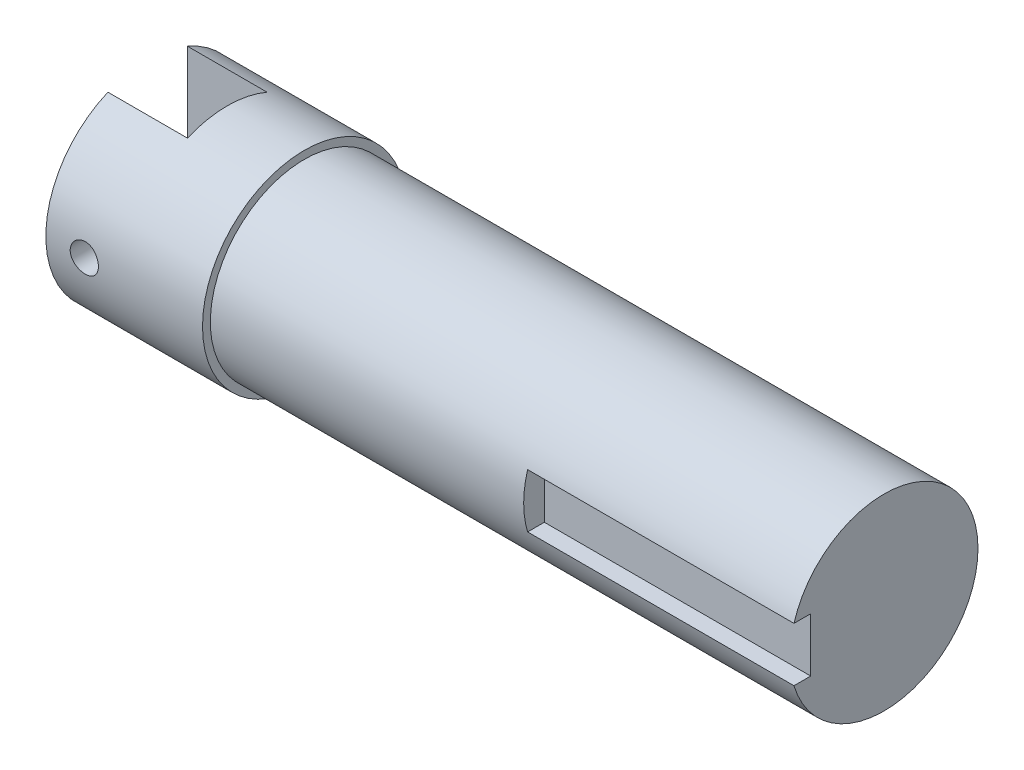
SolidWorks part; units mm, degrees
ref_plane "Front Plane" through (0, 0, 0) normal (1, 0, 0) x (0, 1, 0)
ref_plane "Top Plane" through (0, 0, 0) normal (0, 0, 1) x (0, 1, 0)
ref_plane "Right Plane" through (0, 0, 0) normal (0, 1, 0) x (-1, 0, 0)
sketch "Sketch1" plane through (0, 0, 0) normal (1, 0, 0) x (0, 1, 0)
  circle A0 centre (0, 0) radius 30
  dimension "D1" = 60
extrude "Boss-Extrude1" add sketch "Sketch1" along normal blind 185
sketch "Sketch2" plane through (0, 0, 0) normal (-1, 0, 0) x (0, 0, 1)
  circle A0 centre (0, 0) radius 32.5
  dimension "D1" = 65
extrude "Boss-Extrude2" add sketch "Sketch2" along normal blind 50
sketch "Sketch3" plane through (185, 0, 0) normal (1, 0, 0) x (0, 1, 0)
  line L0 (0, 30) -> (0, 23.4) construction
  line L1 (-8.6135, 34.4) -> (8.6135, 34.4)
  line L2 (-8.6135, 34.4) -> (-8.6135, 23.4)
  line L3 (-8.6135, 23.4) -> (8.6135, 23.4)
  line L4 (8.6135, 34.4) -> (8.6135, 23.4)
  circle A4 centre (0, 0) radius 30 construction
  circle A5 centre (0, 0) radius 30 construction
  point P4 (0, 23.4)
  dimension "D1" = 17.227
  dimension "D3" = 6.6
  dimension "D2" = 11
extrude "Cut-Extrude1" cut sketch "Sketch3" against normal blind 85
sketch "Sketch6" plane through (-50, 0, 0) normal (-1, 0, 0) x (0, -1, 0)
  line L1 (-45.1644, 12.7) -> (51.9653, 12.7)
  line L2 (-45.1644, 12.7) -> (-45.1644, -12.7)
  line L3 (-45.1644, -12.7) -> (51.9653, -12.7)
  line L4 (51.9653, 12.7) -> (51.9653, -12.7)
  point P4 (-45.1644, 0)
  dimension "D1" = 25.4
  dimension "D2" = 45.1644
  dimension "D3" = 0
extrude "Cut-Extrude2" cut sketch "Sketch6" against normal blind 25.4 contours L1 L4 L3 L2
sketch "Sketch7" plane through (0, 0, -12.7) normal (0, 0, 1) x (1, 0, 0)
  circle A0 centre (-37.7298, 0) radius 4.5
extrude "Cut-Extrude3" cut sketch "Sketch7" against normal blind 25.4 and the other way blind 66.4
